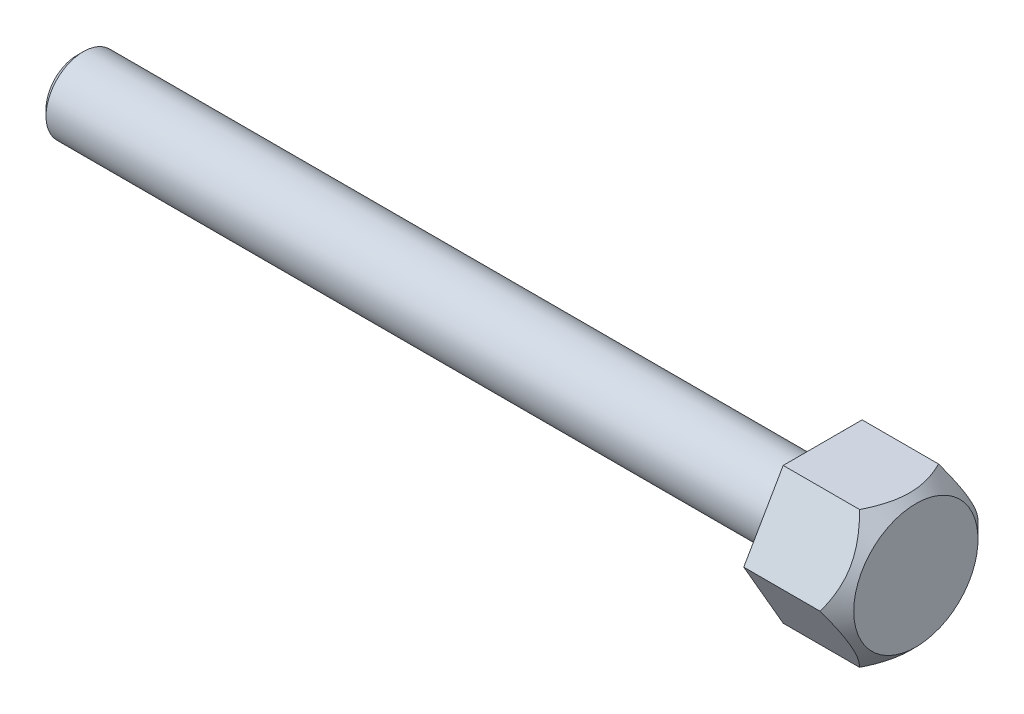
SolidWorks part; units mm, degrees
material "1023 Carbon Steel Sheet (SS)"
ref_plane "Ebene vorne" through (0, 0, 0) normal (0, 0, 1) x (1, 0, 0)
ref_plane "Ebene oben" through (0, 0, 0) normal (0, 1, 0) x (1, 0, 0)
ref_plane "Ebene rechts" through (0, 0, 0) normal (1, 0, 0) x (0, 0, -1)
sketch "Sketch1" plane through (0, 0, 0) normal (0, 0, 1) x (1, 0, 0)
  line L0 (0, 0) -> (0, 1.5)
  line L1 (0, 1.5) -> (-29.75, 1.5)
  line L2 (-29.75, 1.5) -> (-30, 1.25)
  line L3 (-30, 1.25) -> (-30, 0)
  line L4 (-30, 0) -> (0, 0)
  dimension "D1" = 1.5
  dimension "D2" = 135
  dimension "D3" = 1.25
  dimension "D4" = 30
revolve "Revolve1" add sketch "Sketch1" angle 360 about L4
sketch "Sketch2" plane through (0, 0, 0) normal (1, 0, 0) x (0, 0, -1)
  line L0 (-1.5877, 2.75) -> (0, 2.75)
  line L1 (0, 2.75) -> (1.5877, 2.75)
  line L2 (1.5877, 2.75) -> (2.3816, 1.375)
  line L3 (2.3816, 1.375) -> (3.1754, 0)
  line L4 (3.1754, 0) -> (2.3816, -1.375)
  line L5 (2.3816, -1.375) -> (1.5877, -2.75)
  line L6 (1.5877, -2.75) -> (0, -2.75)
  line L7 (0, -2.75) -> (-1.5877, -2.75)
  line L8 (-1.5877, -2.75) -> (-2.3816, -1.375)
  line L9 (-2.3816, -1.375) -> (-3.1754, 0)
  line L10 (-3.1754, 0) -> (-2.3816, 1.375)
  line L11 (-2.3816, 1.375) -> (-1.5877, 2.75)
  circle A0 centre (0, 0) radius 2.75 construction
  dimension "D1" = 5.5
extrude "Boss-Extrude1" add sketch "Sketch2" along normal blind 3.75
sketch "Sketch3" plane through (0, 0, 0) normal (0, 0, 1) x (1, 0, 0)
  line L0 (0, 0) -> (4, 0) construction
  line L1 (4, 0) -> (4, -2.25) construction
  line L2 (4, -2.25) -> (3.5, -2.75)
  line L3 (3.5, -2.75) -> (4, -2.75) construction
  line L4 (4, -2.75) -> (4, -2.25) construction
  line L5 (3.5, -2.75) -> (2.25, -4)
  line L6 (2.25, -4) -> (5.25, -4)
  line L7 (5.25, -4) -> (5.25, -1)
  line L8 (5.25, -1) -> (4, -2.25)
  dimension "D1" = 0.5
  dimension "D2" = 2.25
  dimension "D3" = 4
  dimension "D4" = 3
revolve "Cut-Revolve3" cut sketch "Sketch3" angle 360 about L0
